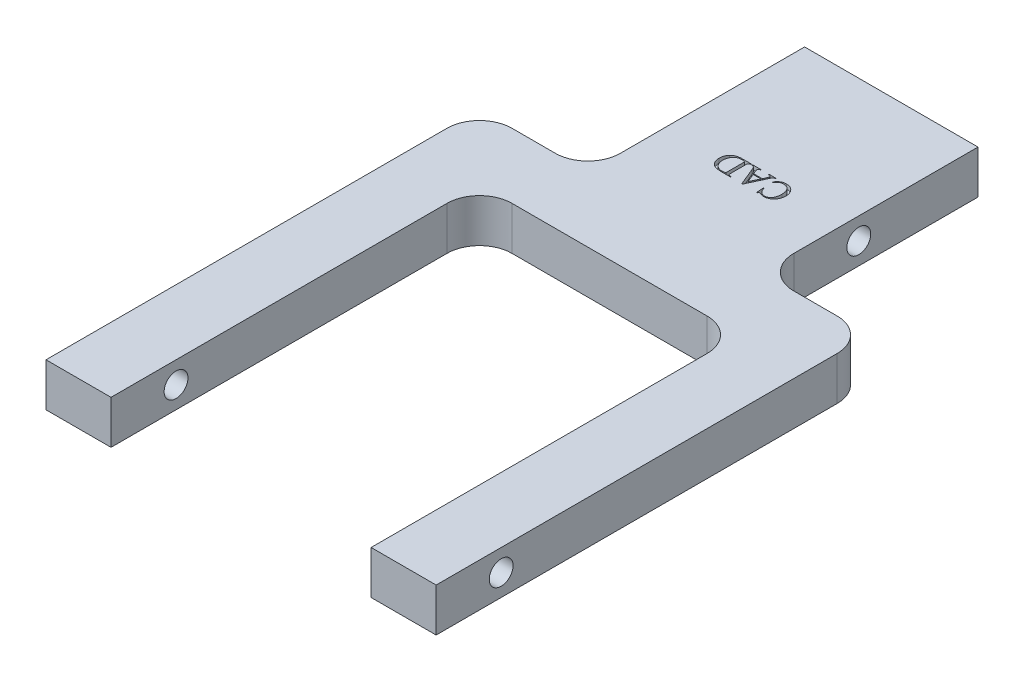
SolidWorks part; units mm, degrees
ref_plane "Front Plane" through (0, 0, 0) normal (0, 0, 1) x (1, 0, 0)
ref_plane "Top Plane" through (0, 0, 0) normal (0, 1, 0) x (1, 0, 0)
ref_plane "Right Plane" through (0, 0, 0) normal (1, 0, 0) x (0, 0, -1)
sketch "Sketch1" plane through (0, 0, 0) normal (0, 0, 1) x (1, 0, 0)
  line L1 (-20, 5) -> (20, 5)
  line L2 (-20, 5) -> (-20, -5)
  line L3 (-20, -5) -> (20, -5)
  line L4 (20, 5) -> (20, -5)
  line L5 (-20, 5) -> (20, -5) construction
  line L6 (-20, -5) -> (20, 5) construction
  point P0 (0, 0)
  dimension "D1" = 40
  dimension "D2" = 10
extrude "Boss-Extrude1" add sketch "Sketch1" along normal mid plane 50
sketch "Sketch2" plane through (20, 0, 0) normal (1, 0, 0) x (0, 0, -1)
  line L0 (25, -5) -> (25, 5) construction
  line L1 (-25, -5) -> (25, -5) construction
  circle A0 centre (-2.5, 0) radius 2.75
  dimension "D1" = 5.5
  dimension "D2" = 27.5
  dimension "D3" = 5
extrude "Cut-Extrude1" cut sketch "Sketch2" against normal through all
sketch "Sketch3" plane through (0, 0, -25) normal (0, 0, -1) x (-1, 0, 0)
  line L1 (-15, 1.75) -> (15, 1.75)
  line L2 (-15, 1.75) -> (-15, -1.75)
  line L3 (-15, -1.75) -> (15, -1.75)
  line L4 (15, 1.75) -> (15, -1.75)
  line L5 (-15, 1.75) -> (15, -1.75) construction
  line L6 (-15, -1.75) -> (15, 1.75) construction
  point P0 (0, 0)
  dimension "D1" = 3.5
  dimension "D2" = 30
extrude "Cut-Extrude5" cut sketch "Sketch3" against normal blind 15 contours L2 L1 L4 L3
sketch "Sketch4" plane through (0, 0, 25) normal (0, 0, 1) x (1, 0, 0)
  line L1 (-45, 5) -> (45, 5)
  line L2 (-45, 5) -> (-45, -5)
  line L3 (-45, -5) -> (45, -5)
  line L4 (45, 5) -> (45, -5)
  line L5 (-45, 5) -> (45, -5) construction
  line L6 (-45, -5) -> (45, 5) construction
  point P0 (0, 0)
  dimension "D1" = 10
  dimension "D2" = 90
extrude "Boss-Extrude2" add sketch "Sketch4" along normal blind 15
sketch "Sketch5" plane through (0, 0, 40) normal (0, 0, 1) x (1, 0, 0)
  line L0 (-45, -5) -> (45, -5) construction
  line L1 (45, 5) -> (30, 5)
  line L2 (45, 5) -> (45, -5)
  line L3 (45, -5) -> (30, -5)
  line L4 (30, 5) -> (30, -5)
  line L5 (45, 5) -> (30, -5) construction
  line L6 (45, -5) -> (30, 5) construction
  line L7 (0, 0) -> (0, 5) construction
  line L8 (45, 5) -> (-45, 5) construction
  line L9 (-45, -5) -> (-30, -5)
  line L10 (-30, 5) -> (-30, -5)
  line L11 (-45, 5) -> (-30, 5)
  line L12 (-45, 5) -> (-45, -5)
  point P4 (37.5, 0)
  dimension "D1" = 15
extrude "Boss-Extrude3" add sketch "Sketch5" along normal blind 85
sketch "Sketch6" plane through (45, 0, 0) normal (1, 0, 0) x (0, 0, -1)
  line L0 (-125, -5) -> (-125, 5) construction
  line L1 (-125, -5) -> (-25, -5) construction
  circle A0 centre (-110, 0) radius 2.75
  dimension "D1" = 5.5
  dimension "D2" = 15
  dimension "D3" = 5
extrude "Cut-Extrude6" cut sketch "Sketch6" against normal through all
fillet "Fillet3" radius 7.5 6 edges at (-30, 0, 40) (45, 0, 25) (20, 0, 25) (-45, 0, 25) (-20, 0, 25) (30, 0, 40)
sketch "Sketch7" plane through (0, 5, 0) normal (0, 1, 0) x (1, 0, 0)
  line L0 (-20, -4.5388) -> (20, -4.5388) construction
  line L1 (-20, -17.5) -> (-20, 25) construction
  line L2 (20, -17.5) -> (20, 25) construction
  text T0 "CAD" font "Times New Roman" height 5
extrude "Cut-Extrude7" cut sketch "Sketch7" against normal blind 1
